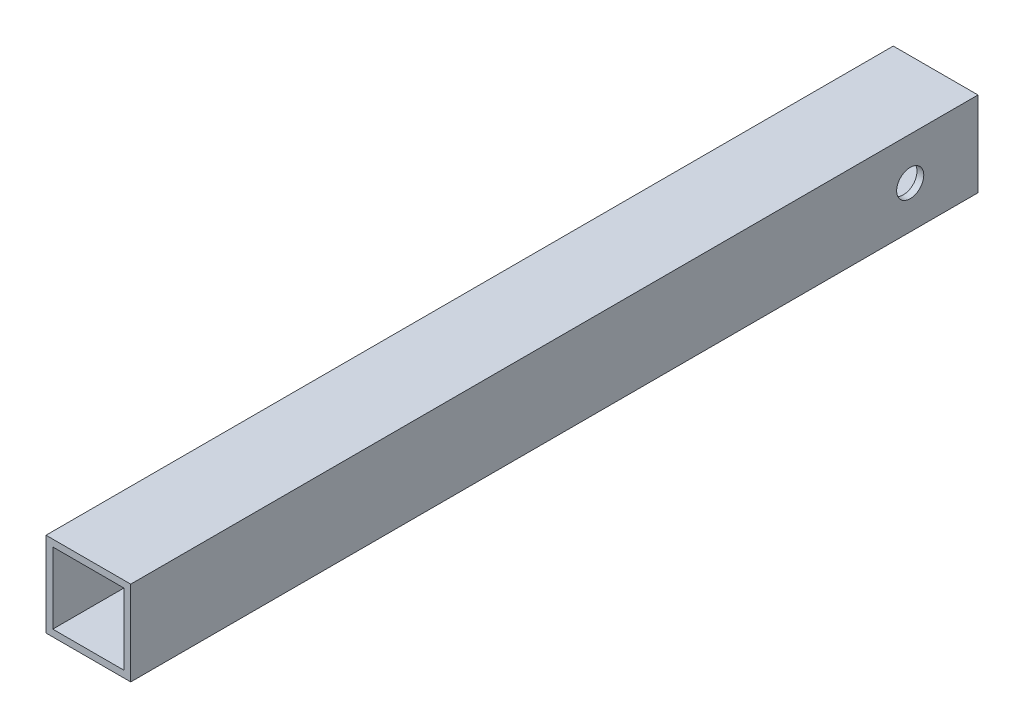
SolidWorks part; units mm, degrees
ref_plane "Front Plane" through (0, 0, 0) normal (0, 0, 1) x (1, 0, 0)
ref_plane "Top Plane" through (0, 0, 0) normal (0, 1, 0) x (1, 0, 0)
ref_plane "Right Plane" through (0, 0, 0) normal (1, 0, 0) x (0, 0, -1)
sketch "Sketch2" plane through (0, 0, 0) normal (0, 0, 1) x (1, 0, 0)
  line L1 (-12.5, -12.5) -> (12.5, -12.5)
  line L2 (-12.5, -12.5) -> (-12.5, 12.5)
  line L3 (-12.5, 12.5) -> (12.5, 12.5)
  line L4 (12.5, -12.5) -> (12.5, 12.5)
  line L5 (-12.5, -12.5) -> (12.5, 12.5) construction
  line L6 (-12.5, 12.5) -> (12.5, -12.5) construction
  point P0 (0, 0)
  dimension "D1" = 25
  dimension "D2" = 25
extrude "Extrude-Thin1" add sketch "Sketch2" along normal mid plane 250 thin thin type one direction reverse wall 2
sketch "Sketch3" plane through (12.5, 0, 0) normal (1, 0, 0) x (0, 0, -1)
  line L1 (13.75, 0) -> (-13.75, 0) construction
  line L2 (125, -12.5) -> (125, 12.5) construction
  circle A0 centre (105, 0) radius 4
  dimension "D1" = 8
  dimension "D2" = 20
extrude "hole" cut sketch "Sketch3" against normal through all
sketch "Sketch4" [suppressed] plane through (0, 12.5, 0) normal (0, 1, 0) x (1, 0, 0)
  circle A0 centre (0, 0) radius 8
  dimension "D1" = 16
extrude "Cut-Extrude1" [suppressed] cut sketch "Sketch4" against normal through all
